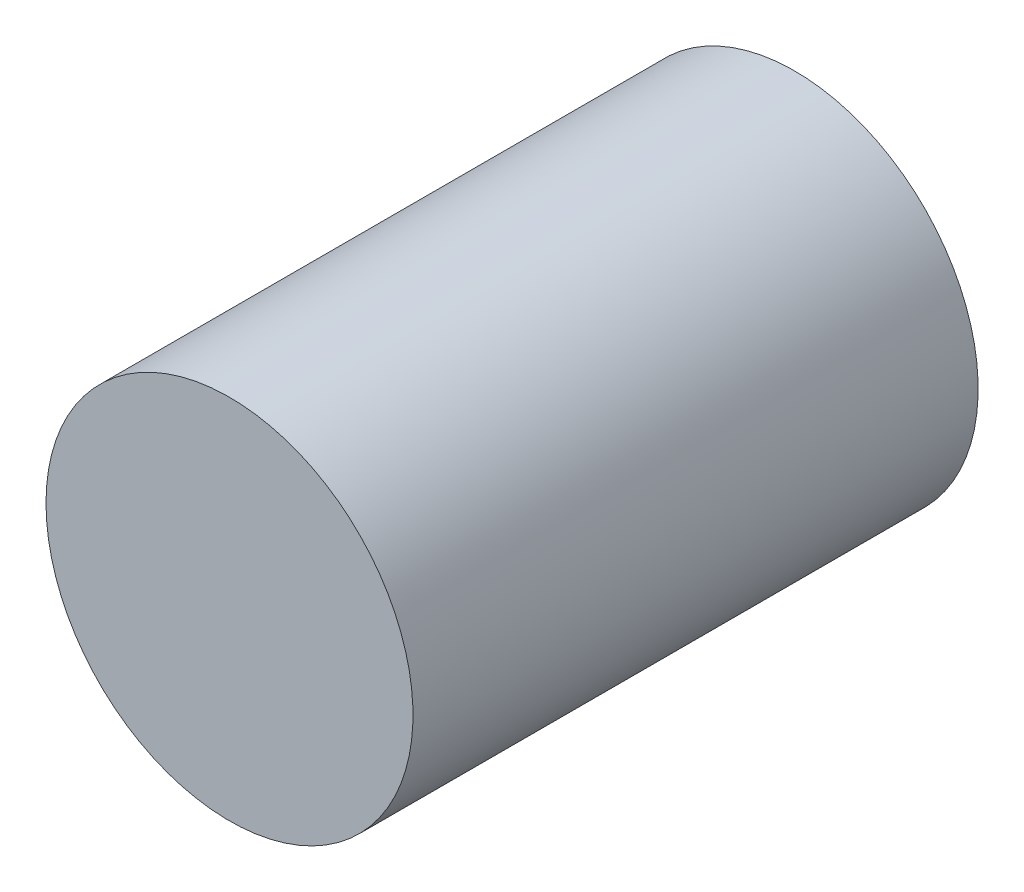
SolidWorks part; units mm, degrees
ref_plane "Front Plane" through (0, 0, 0) normal (0, 0, 1) x (1, 0, 0)
ref_plane "Top Plane" through (0, 0, 0) normal (0, 1, 0) x (1, 0, 0)
ref_plane "Right Plane" through (0, 0, 0) normal (1, 0, 0) x (0, 0, -1)
sketch "Sketch1" plane through (0, 0, 0) normal (0, 1, 0) x (1, 0, 0)
  line L0 (0, 73.0366) -> (0, 41.0366)
  line L1 (0, 41.0366) -> (-9.5, 41.0366)
  line L2 (-9.5, 41.0366) -> (-9.5, 38.0366)
  line L3 (-9.5, 38.0366) -> (-20, 38.0366)
  line L4 (-20, 38.0366) -> (-20, 8.0366)
  line L5 (-20, 8.0366) -> (-9.5, 8.0366)
  line L6 (-9.5, 8.0366) -> (-9.5, 5.0366)
  line L7 (-9.5, 5.0366) -> (0, 5.0366)
  line L8 (0, 5.0366) -> (0, -26.9634)
  line L9 (0, -26.9634) -> (-32.4666, -26.9634)
  line L10 (-32.4666, -26.9634) -> (-32.4666, 73.0366)
  line L11 (-32.4666, 73.0366) -> (0, 73.0366)
  dimension "D1" = 20
  dimension "D2" = 9.5
  dimension "D3" = 3
  dimension "D4" = 3
  dimension "D5" = 9.5
  dimension "D6" = 30
  dimension "D7" = 100
revolve "Revolve1" add sketch "Sketch1" angle 360 about L8
